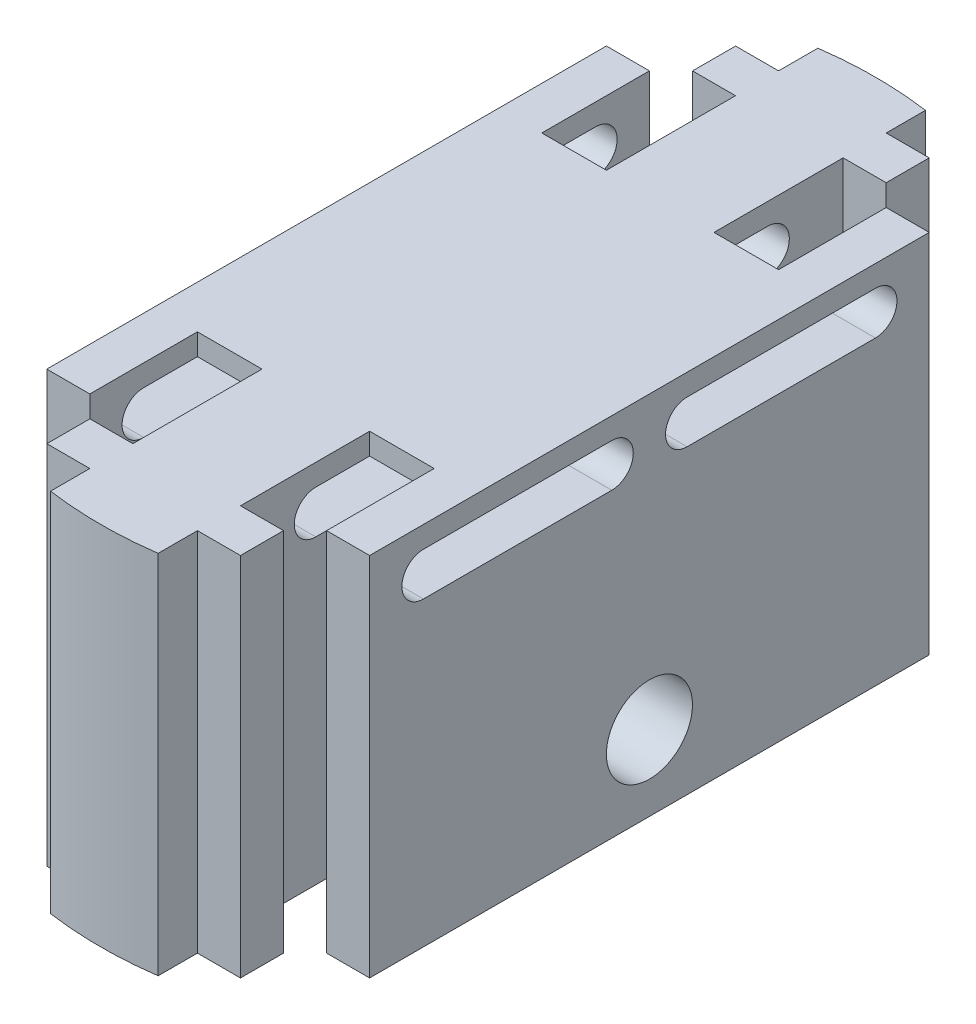
SolidWorks part; units mm, degrees
ref_plane "前视基准面" through (0, 0, 0) normal (0, 0, 1) x (1, 0, 0)
ref_plane "上视基准面" through (0, 0, 0) normal (0, 1, 0) x (1, 0, 0)
ref_plane "右视基准面" through (0, 0, 0) normal (1, 0, 0) x (0, 0, -1)
other "Configuration Table"
sketch "草图8" plane through (0, 0, 0) normal (0, 1, 0) x (1, 0, 0)
  line L0 (-1000, 0) -> (49000, 0) construction
  line L2 (4.5, -16) -> (2.5, -16)
  line L3 (0, 13) -> (0, 16) construction
  line L4 (-2.5, 16) -> (2.5, 16) construction
  line L5 (2.5, 13) -> (2.5, 14)
  line L6 (2.5, 14) -> (4.5, 14)
  line L7 (4.5, 14) -> (4.5, 16)
  line L8 (4.5, 16) -> (2.5, 16)
  line L9 (2.5, 16) -> (2.5, 17.8255)
  line L10 (-2.5, 17.8255) -> (-2.5, 16)
  line L11 (-2.5, 16) -> (-4.4964, 16)
  line L12 (-4.4964, 16) -> (-4.4964, 14)
  line L13 (-4.4964, 14) -> (-2.5, 14)
  line L14 (-2.5, 14) -> (-2.5, 13)
  line L16 (4.5, -14) -> (4.5, -16)
  line L17 (2.5, -13) -> (2.5, -14)
  line L18 (2.5, -14) -> (4.5, -14)
  line L19 (2.5, -16) -> (2.5, -17.8255)
  line L20 (-2.5, -17.8255) -> (-2.5, -16)
  line L21 (-2.5, -16) -> (-4.4964, -16)
  line L22 (-4.4964, -16) -> (-4.4964, -14)
  line L23 (-4.4964, -14) -> (-2.5, -14)
  line L24 (-2.5, -14) -> (-2.5, -13)
  line L25 (-2.5, -13) -> (-2.5, 13)
  line L26 (2.5, -13) -> (2.5, 13)
  arc A0 (-2.5, -17.8255) -> (2.5, -17.8255) centre (0, 0) ccw
  arc A1 (2.5, 17.8255) -> (-2.5, 17.8255) centre (0, 0) ccw
  point P14 (0, 16)
  dimension "D1" = 36
  dimension "D4" = 3
  dimension "D5" = 5
  dimension "D6" = 1
  dimension "D7" = 1.9964
  dimension "D8" = 2
  dimension "D9" = 2
  dimension "D10" = 8.9964
extrude "凸台-拉伸7" add sketch "草图8" along normal blind 7
sketch "草图11" plane through (0, 0, 0) normal (0, 1, 0) x (1, 0, 0)
  line L0 (2.5, -14) -> (2.5, 14) construction
  line L1 (-2.5, 8) -> (2.5, 8)
  line L2 (-2.5, 8) -> (-2.5, -8)
  line L3 (-2.5, -8) -> (2.5, -8)
  line L4 (2.5, 8) -> (2.5, -8)
  line L5 (-2.5, 8) -> (2.5, -8) construction
  line L6 (-2.5, -8) -> (2.5, 8) construction
  point P0 (0, 0)
  dimension "D1" = 16
extrude "凸台-拉伸8" add sketch "草图11" along normal blind 10 from surface at 7 starting at face at (0.0007, 7, 0)
sketch "草图14" plane through (0, 0, 0) normal (0, 1, 0) x (1, 0, 0)
  line L0 (2.5, -14) -> (2.5, -8) construction
  line L2 (-2.5, -8) -> (-2.5, -14) construction
  line L3 (-2.5, -14) -> (-4.4964, -14) construction
  line L4 (-4.4964, -14) -> (-4.4964, -16) construction
  line L5 (-4.4964, -16) -> (-2.5, -16) construction
  line L6 (-2.5, -16) -> (-2.5, -17.8255) construction
  line L7 (2.5, -17.8255) -> (2.5, -16) construction
  line L8 (2.5, -16) -> (4.5, -16) construction
  line L9 (4.5, -16) -> (4.5, -14) construction
  line L10 (4.5, -14) -> (2.5, -14) construction
  line L15 (-2.5, 14) -> (-2.5, 8) construction
  line L17 (2.5, 8) -> (2.5, 14) construction
  line L18 (2.5, 14) -> (4.5, 14) construction
  line L19 (4.5, 14) -> (4.5, 16) construction
  line L20 (4.5, 16) -> (2.5, 16) construction
  line L21 (2.5, 16) -> (2.5, 17.8255) construction
  line L22 (-2.5, 17.8255) -> (-2.5, 16) construction
  line L23 (-2.5, 16) -> (-4.4964, 16) construction
  line L24 (-4.4964, 16) -> (-4.4964, 14) construction
  line L25 (-4.4964, 14) -> (-2.5, 14) construction
  line L26 (2.5, -14) -> (2.5, -8)
  line L28 (-2.5, -8) -> (-2.5, -14)
  line L29 (-2.5, -14) -> (-4.4964, -14)
  line L30 (-4.4964, -14) -> (-4.4964, -16)
  line L31 (-4.4964, -16) -> (-2.5, -16)
  line L32 (-2.5, -16) -> (-2.5, -17.8255)
  line L33 (2.5, -17.8255) -> (2.5, -16)
  line L34 (2.5, -16) -> (4.5, -16)
  line L35 (4.5, -16) -> (4.5, -14)
  line L36 (4.5, -14) -> (2.5, -14)
  line L41 (-2.5, 14) -> (-2.5, 8)
  line L43 (2.5, 8) -> (2.5, 14)
  line L44 (2.5, 14) -> (4.5, 14)
  line L45 (4.5, 14) -> (4.5, 16)
  line L46 (4.5, 16) -> (2.5, 16)
  line L47 (2.5, 16) -> (2.5, 17.8255)
  line L48 (-2.5, 17.8255) -> (-2.5, 16)
  line L49 (-2.5, 16) -> (-4.4964, 16)
  line L50 (-4.4964, 16) -> (-4.4964, 14)
  line L51 (-4.4964, 14) -> (-2.5, 14)
  line L52 (7.5, 13) -> (7.5, -13)
  line L53 (7.5, -13) -> (5.5, -13)
  line L54 (7.5, 13) -> (5.5, 13)
  line L55 (2.5, 8) -> (5.5, 8)
  line L56 (5.5, 8) -> (5.5, 13)
  line L57 (5.5, -13) -> (5.5, -8)
  line L58 (5.5, -8) -> (2.5, -8)
  line L59 (5.5, -8) -> (2.5, -8)
  line L60 (5.5, 8) -> (2.5, 8)
  line L61 (5.5, -8) -> (2.5, -8)
  line L62 (0, -1000) -> (0, 49000) construction
  line L63 (-5.5, -8) -> (-2.5, -8)
  line L64 (-5.5, 8) -> (-2.5, 8)
  line L65 (-5.5, -8) -> (-2.5, -8)
  line L66 (-5.5, -8) -> (-2.5, -8)
  line L67 (-5.5, -13) -> (-5.5, -8)
  line L68 (-5.5, 8) -> (-5.5, 13)
  line L69 (-2.5, 8) -> (-5.5, 8)
  line L70 (-7.5, 13) -> (-5.5, 13)
  line L71 (-7.5, -13) -> (-5.5, -13)
  line L72 (-7.5, 13) -> (-7.5, -13)
  arc A0 (-2.5, -17.8255) -> (2.5, -17.8255) centre (0, 0) ccw construction
  arc A1 (2.5, 17.8255) -> (-2.5, 17.8255) centre (0, 0) ccw construction
  arc A2 (-2.5, -17.8255) -> (2.5, -17.8255) centre (0, 0) ccw
  arc A3 (2.5, 17.8255) -> (-2.5, 17.8255) centre (0, 0) ccw
  dimension "D1" = 5
  dimension "D2" = 5
  dimension "D3" = 3
  dimension "D4" = 3
  dimension "D5" = 2
  dimension "D6" = 5.5
  dimension "D7" = 16
extrude "凸台-拉伸10" add sketch "草图14" along normal up to surface (17 mm away) contours A2 L62 A3 L48 L49 L50 L51 L41 L64 L68 L70 L72 L71 L67 L63 L28 L29 L30 L31 L32 | L62 A2 L33 L34 L35 L36 L26 L58 L57 L53 L52 L54 L56 L55 L43 L44 L45 L46 L47 A3 up to face at (0, 17, 0)
sketch "草图15" plane through (0, 0, 0) normal (1, 0, 0) x (0, 0, -1)
  line L0 (0, 0) -> (0, 3.5) construction
  circle A0 centre (0, 3.5) radius 2
  dimension "D2" = 4
  dimension "D1" = 3.5
extrude "切除-拉伸1" cut sketch "草图15" against normal through all and the other way through all
sketch "草图17" plane through (0, 0, 0) normal (1, 0, 0) x (0, 0, -1)
  line L0 (0, 0) -> (0, 10) construction
  line L2 (13, 0) -> (-13, 0) construction
  line L3 (-13, 17) -> (-13, 0) construction
  line L4 (-10.5, 15) -> (-1.75, 15) construction
  line L5 (-10.5, 16) -> (-1.75, 16)
  line L6 (-1.75, 14) -> (-10.5, 14)
  line L7 (10.5, 15) -> (1.75, 15) construction
  line L8 (1.75, 14) -> (10.5, 14)
  line L9 (10.5, 16) -> (1.75, 16)
  arc A0 (-10.5, 16) -> (-10.5, 14) centre (-10.5, 15) ccw
  arc A1 (-1.75, 14) -> (-1.75, 16) centre (-1.75, 15) ccw
  arc A2 (1.75, 14) -> (1.75, 16) centre (1.75, 15) cw
  arc A3 (10.5, 16) -> (10.5, 14) centre (10.5, 15) cw
  point P21 (10.5, 15)
  dimension "D2" = 2
  dimension "D6" = 2
  dimension "D1" = 10
  dimension "D3" = 2.5
  dimension "D4" = 15
  dimension "D5" = 8.75
extrude "切除-拉伸2" cut sketch "草图17" against normal through all and the other way through all
